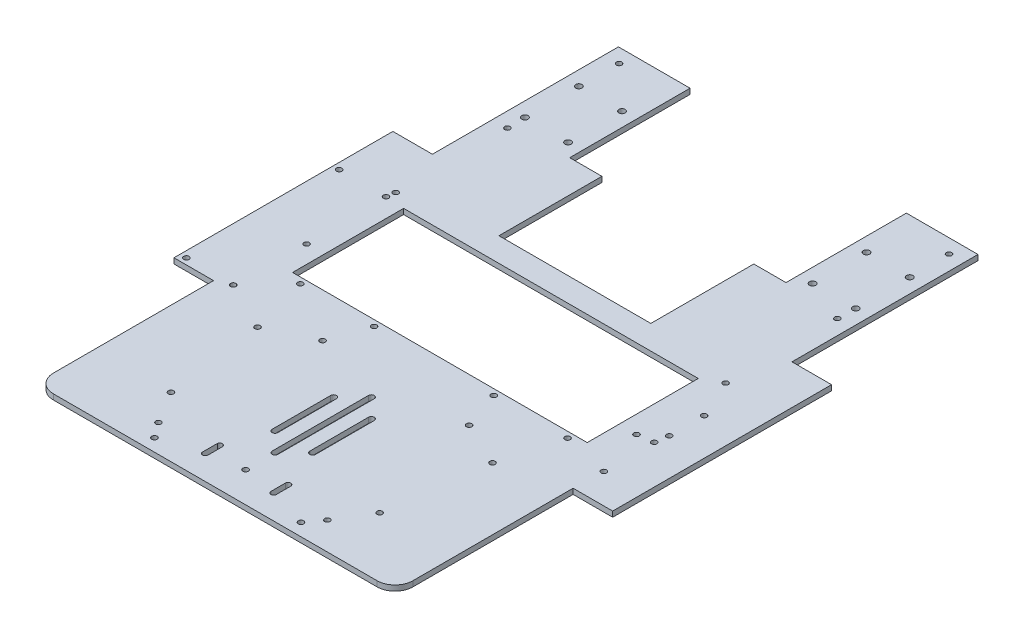
SolidWorks part; units mm, degrees
material "1060 合金"
ref_plane "前视基准面" through (0, 0, 0) normal (0, 0, 1) x (1, 0, 0)
ref_plane "上视基准面" through (0, 0, 0) normal (0, 1, 0) x (1, 0, 0)
ref_plane "右视基准面" through (0, 0, 0) normal (1, 0, 0) x (0, 0, -1)
sketch "草图1" plane through (0, 0, 0) normal (0, 1, 0) x (1, 0, 0)
  line L1 (-100, 187.5) -> (100, 187.5)
  line L2 (-100, 187.5) -> (-100, -187.5)
  line L3 (-100, -187.5) -> (100, -187.5)
  line L4 (100, 187.5) -> (100, -187.5)
  line L5 (-100, 187.5) -> (100, -187.5) construction
  line L6 (-100, -187.5) -> (100, 187.5) construction
  point P0 (0, 0)
  dimension "D1" = 200
  dimension "D2" = 375
extrude "凸台-拉伸1" add sketch "草图1" along normal blind 3
sketch "草图2" plane through (0, 0, 0) normal (0, -1, 0) x (1, 0, 0)
  circle A0 centre (-68, -157.5) radius 1.75
  circle A1 centre (-92, -157.5) radius 1.75
  circle A2 centre (-92, -127.5) radius 1.75
  circle A3 centre (-68, -127.5) radius 1.75
  circle A4 centre (68, -157.5) radius 1.75
  circle A5 centre (92, -157.5) radius 1.75
  circle A6 centre (92, -127.5) radius 1.75
  circle A7 centre (68, -127.5) radius 1.75
extrude "切除-拉伸1" cut sketch "草图2" against normal blind 10
sketch "草图3" plane through (0, 3, 0) normal (0, 1, 0) x (1, 0, 0)
  line L0 (-105, 142.5) -> (105, 142.5) construction
  line L1 (0, 142.5) -> (0, -119.8967) construction
  line L2 (89.8494, 24.4347) -> (-12.8649, 220.1986) construction
  circle A0 centre (0, -119.8967) radius 1.5
  dimension "D1" = 3
extrude "切除-拉伸2" cut sketch "草图3" against normal blind 10
sketch "草图4" plane through (0, 3, 0) normal (0, 1, 0) x (1, 0, 0)
  line L0 (0, -119.8967) -> (19, -119.8967) construction
  circle A0 centre (19, -119.8967) radius 1.5
  circle A1 centre (-19, -119.8967) radius 1.5
  point P4 (0, -119.8967)
  dimension "D2" = 3
  dimension "D3" = 3
  dimension "D4" = 19
  dimension "D1" = 19
extrude "切除-拉伸3" cut sketch "草图4" against normal blind 10
sketch "草图5" plane through (0, 0, 0) normal (0, -1, 0) x (1, 0, 0)
  line L0 (0, 187.5) -> (0, 136.7741) construction
  line L1 (-100, 187.5) -> (100, 187.5) construction
  line L3 (-105, 136.7741) -> (105, 136.7741)
  line L4 (-105, 136.7741) -> (-105, 187.5)
  line L5 (-105, 187.5) -> (105, 187.5)
  line L6 (105, 136.7741) -> (105, 187.5)
  line L7 (-105, 136.7741) -> (105, 187.5) construction
  line L8 (-105, 187.5) -> (105, 136.7741) construction
  point P5 (0, 162.1371)
  dimension "D1" = 210
extrude "切除-拉伸5" cut sketch "草图5" against normal blind 34.39
sketch "草图8" plane through (-100, 0, 0) normal (-1, 0, 0) x (0, 0, 1)
  line L0 (-162.3927, 122.6166) -> (228.9407, 122.6166) construction
  line L1 (31.5492, 79.1374) -> (31.5492, -133.9071) construction
  line L2 (31.5492, -13.3403) -> (-28.0757, -13.3403) construction
  line L3 (-31.7127, 11.4579) -> (-31.7127, -35.1628) construction
  line L4 (-89.9817, 86.9955) -> (-89.9817, -35.1628) construction
  line L5 (34.4197, 14.3679) -> (37.8722, 3)
  line L6 (136.7741, 3) -> (-187.5, 3) construction
  line L7 (37.8722, 3) -> (25.2261, 3)
  line L8 (28.6786, 14.3679) -> (25.2261, 3)
  arc A0 (34.4197, 14.3679) -> (28.6786, 14.3679) centre (31.5492, 13.4961) ccw
  circle A1 centre (31.5492, 13.4961) radius 1.5
  point P19 (31.5492, 3)
  dimension "D1" = 6
  dimension "D2" = 3
extrude "凸台-拉伸2" add sketch "草图8" against normal blind 3
sketch "草图9" plane through (0, 0, 0) normal (0, -1, 0) x (1, 0, 0)
  line L1 (-81.9415, -19.3479) -> (81.9415, -19.3479)
  line L2 (-81.9415, -19.3479) -> (-81.9415, 55.6521)
  line L3 (-81.9415, 55.6521) -> (81.9415, 55.6521)
  line L4 (81.9415, -19.3479) -> (81.9415, 55.6521)
  line L5 (-81.9415, -19.3479) -> (81.9415, 55.6521) construction
  line L6 (-81.9415, 55.6521) -> (81.9415, -19.3479) construction
  point P0 (0, 18.1521)
  dimension "D1" = 75
extrude "切除-拉伸6" cut sketch "草图9" against normal blind 10
sketch "草图10" plane through (0, 0, 0) normal (0, -1, 0) x (1, 0, 0)
  line L0 (0, -63.2891) -> (0, -187.5) construction
  line L1 (100, -187.5) -> (-100, -187.5) construction
  line L2 (-60.1571, -120.5533) -> (-42.2388, -120.5533)
  line L4 (-60.1571, -120.5533) -> (-60.1571, -187.5)
  line L5 (-60.1571, -187.5) -> (60.1571, -187.5)
  line L6 (60.1571, -120.5533) -> (60.1571, -187.5)
  line L7 (-42.2388, -68.35) -> (60.1571, -187.5) construction
  line L8 (-60.1571, -187.5) -> (42.2388, -68.35) construction
  line L9 (-42.2388, -120.5533) -> (-42.2388, -63.2891)
  line L10 (-42.2388, -63.2891) -> (42.2388, -63.2891)
  line L11 (42.2388, -120.5533) -> (42.2388, -63.2891)
  line L12 (60.1571, -120.5533) -> (42.2388, -120.5533)
  point P4 (0, -117.5)
extrude "切除-拉伸7" cut sketch "草图10" against normal blind 3
sketch "草图11" plane through (0, 3, 0) normal (0, 1, 0) x (1, 0, 0)
  circle A0 centre (-91.7562, 179.6301) radius 1.5
  circle A1 centre (-91.7562, 117.5) radius 1.5
  circle A2 centre (-91.7562, 55.3699) radius 1.5
  circle A3 centre (91.7562, 55.3699) radius 1.5
  circle A4 centre (91.7562, 117.5) radius 1.5
  circle A5 centre (91.7562, 179.6301) radius 1.5
extrude "切除-拉伸8" cut sketch "草图11" against normal blind 6
sketch "草图12" plane through (0, 3, 0) normal (0, 1, 0) x (1, 0, 0)
  circle A0 centre (-91.7562, 5.8084) radius 1.5
  circle A1 centre (91.7562, 5.8084) radius 1.5
extrude "切除-拉伸9" cut sketch "草图12" against normal blind 3
sketch "草图14" plane through (0, 3, 0) normal (0, 1, 0) x (1, 0, 0)
  line L0 (81.9415, 19.3479) -> (81.9415, 49.289)
  line L1 (-81.9415, 49.289) -> (-81.9415, 54.8514)
  line L2 (-81.9415, 49.289) -> (-81.9415, 19.3479)
  line L3 (-81.9415, 19.3479) -> (81.9415, 19.3479)
  line L5 (-81.9415, 54.8514) -> (81.9415, 54.8514)
  line L6 (81.9415, 54.8514) -> (81.9415, 49.289)
extrude "切除-拉伸10" cut sketch "草图14" against normal blind 163.8
sketch "草图16" plane through (0, 3, 0) normal (0, 1, 0) x (1, 0, 0)
  line L0 (-86.368, -11.8049) -> (87.5033, -11.8049)
  line L1 (87.5033, -11.8049) -> (87.5033, -62.5063)
  line L2 (87.5033, -62.5063) -> (-86.368, -62.5063)
  line L3 (-86.368, -62.5063) -> (-86.368, -11.8049)
extrude "凸台-拉伸4" add sketch "草图16" against normal blind 3
sketch "草图18" plane through (-100, 0, 0) normal (-1, 0, 0) x (0, 0, 1)
  line L0 (-187.5, 3) -> (25.2261, 3) construction
  line L1 (-187.5, 0) -> (136.7741, 0) construction
  line L2 (-84.0425, 3) -> (37.706, 3)
  line L3 (-84.0425, 3) -> (-84.0425, 0)
  line L4 (-84.0425, 0) -> (37.706, 0)
  line L5 (37.706, 3) -> (37.706, 0)
extrude "凸台-拉伸5" add sketch "草图18" along normal blind 22
sketch "草图19" plane through (-100, 0, 0) normal (-1, 0, 0) x (0, 0, 1)
  line L0 (37.8722, 3) -> (136.7741, 3) construction
  line L1 (22.9673, 24.5564) -> (40.2459, 24.5564)
  line L2 (22.9673, 24.5564) -> (22.9673, 3)
  line L3 (22.9673, 3) -> (40.2459, 3)
  line L4 (40.2459, 24.5564) -> (40.2459, 3)
  line L5 (22.9673, 24.5564) -> (40.2459, 3) construction
  line L6 (22.9673, 3) -> (40.2459, 24.5564) construction
  point P0 (31.6066, 13.7782)
extrude "切除-拉伸11" cut sketch "草图19" against normal blind 22
mirror "镜向1" about plane through (0, 0, 0) normal (1, 0, 0) of "凸台-拉伸5"
sketch "草图20" plane through (0, 0, 0) normal (0, -1, 0) x (1, 0, 0)
  circle A0 centre (-92.4373, 34.3016) radius 1.5
  circle A1 centre (-118.5127, 34.3016) radius 1.5
  circle A2 centre (-92.4373, -50.6696) radius 1.5
  circle A3 centre (-118.5127, -50.6696) radius 1.5
extrude "切除-拉伸12" cut sketch "草图20" against normal blind 5
sketch "草图21" plane through (0, 3, 0) normal (0, 1, 0) x (1, 0, 0)
  circle A0 centre (101.4936, 33.6733) radius 1.5
  circle A1 centre (101.4936, 14.236) radius 1.5
  circle A2 centre (100.4679, -21.0893) radius 1.5
  circle A3 centre (100.4679, 6.9384) radius 1.5
  point P12 (0, 0)
  point P13 (0, 0)
  point P14 (0, 0)
  point P15 (0, 0)
extrude "切除-拉伸13" cut sketch "草图21" against normal blind 6
sketch "草图22" plane through (0, 3, 0) normal (0, 1, 0) x (1, 0, 0)
  line L0 (-81.9415, 49.9559) -> (81.9415, 49.9559)
  line L1 (-81.9415, 54.8514) -> (-81.9415, -11.8049) construction
  line L2 (81.9415, -11.8049) -> (81.9415, 54.8514) construction
  line L3 (81.9415, 49.9559) -> (81.9415, 54.8514)
  line L4 (81.9415, 54.8514) -> (-81.9415, 54.8514) construction
  line L5 (81.9415, 54.8514) -> (-81.9415, 54.8514)
  line L6 (-81.9415, 54.8514) -> (-81.9415, 49.9559)
extrude "凸台-拉伸6" add sketch "草图22" against normal up to surface (3 mm away) up to face at (101.4936, 0, -12.736)
sketch "草图23" plane through (0, 0, 0) normal (0, -1, 0) x (1, 0, 0)
  line L0 (0, 76.779) -> (0, 36.8339) construction
  line L1 (-12.1, 93.0464) -> (-12.1, 60.4263)
  line L2 (-8.9, 60.4263) -> (-8.9, 93.0464)
  line L3 (8.9, 93.0464) -> (8.9, 60.4263)
  line L4 (12.1, 60.4263) -> (12.1, 93.0464)
  line L5 (-1.6, 103.5464) -> (-1.6, 49.9263)
  line L6 (1.6, 49.9263) -> (1.6, 103.5464)
  arc A0 (8.9, 60.4263) -> (12.1, 60.4263) centre (10.5, 60.4263) ccw
  arc A1 (-12.1, 60.4263) -> (-8.9, 60.4263) centre (-10.5, 60.4263) ccw
  arc A2 (-1.6, 49.9263) -> (1.6, 49.9263) centre (0, 49.9263) ccw
  arc A4 (-8.9, 93.0464) -> (-12.1, 93.0464) centre (-10.5, 93.0464) ccw
  arc A6 (12.1, 93.0464) -> (8.9, 93.0464) centre (10.5, 93.0464) ccw
  arc A7 (1.6, 103.5464) -> (-1.6, 103.5464) centre (0, 103.5464) ccw
extrude "切除-拉伸14" cut sketch "草图23" against normal blind 10
sketch "草图24" plane through (0, 3, 0) normal (0, 1, 0) x (1, 0, 0)
  line L0 (-20.5, -119.8967) -> (-20.5, -115.1045)
  line L1 (-17.5, -119.8967) -> (-17.5, -115.1045)
  line L2 (-17.5, -119.8967) -> (-17.5, -123.2927)
  line L3 (-20.5, -123.2927) -> (-20.5, -119.8967)
  line L4 (0, -118.3967) -> (0, -124.1043) construction
  line L5 (20.5, -123.2927) -> (20.5, -119.8967)
  line L6 (17.5, -119.8967) -> (17.5, -123.2927)
  line L7 (17.5, -119.8967) -> (17.5, -115.1045)
  line L8 (20.5, -119.8967) -> (20.5, -115.1045)
  circle A0 centre (-19, -119.8967) radius 1.5 construction
  arc A1 (-17.5, -115.4096) -> (-20.5, -115.4096) centre (-19, -115.257) ccw
  arc A2 (-20.5, -123.2927) -> (-17.5, -123.2927) centre (-19, -123.2927) ccw
  circle A3 centre (0, -119.8967) radius 1.5 construction
  arc A4 (20.5, -123.2927) -> (17.5, -123.2927) centre (19, -123.2927) cw
  arc A5 (17.5, -115.4096) -> (20.5, -115.4096) centre (19, -115.257) cw
extrude "切除-拉伸15" cut sketch "草图24" against normal blind 10 contours L3 A2 L2 L1 A1 L0 | A5 L7 L6 A4 L5 L8
sketch "草图25" plane through (0, 3, 0) normal (0, 1, 0) x (1, 0, 0)
  circle A0 centre (-74.308, -15.1266) radius 1.5
  circle A1 centre (-33.25, -15.1266) radius 1.5
  circle A2 centre (33.25, -15.1266) radius 1.5
  circle A3 centre (74.308, -15.1266) radius 1.5
extrude "切除-拉伸16" cut sketch "草图25" against normal blind 5
sketch "草图26" plane through (0, 3, 0) normal (0, 1, 0) x (1, 0, 0)
  circle A0 centre (-65.342, -47.8897) radius 1.5
  circle A1 centre (65.342, -47.8897) radius 1.5
  circle A2 centre (46.9865, -121.3869) radius 1.5
  circle A3 centre (-46.9865, -121.3869) radius 1.5
extrude "切除-拉伸17" cut sketch "草图26" against normal blind 10
sketch "草图27" plane through (0, 3, 0) normal (0, 1, 0) x (1, 0, 0)
  line L0 (0, -158.3179) -> (0, -24.9992) construction
  line L2 (-40.75, -36.322) -> (40.75, -36.322) construction
  line L3 (-40.75, -36.322) -> (-40.75, -129.822) construction
  line L4 (-40.75, -129.822) -> (40.75, -129.822) construction
  line L5 (40.75, -36.322) -> (40.75, -129.822) construction
  line L6 (-40.75, -36.322) -> (40.75, -129.822) construction
  line L7 (-40.75, -129.822) -> (40.75, -36.322) construction
  circle A0 centre (-40.75, -36.322) radius 1.5
  circle A1 centre (40.75, -36.322) radius 1.5
  circle A2 centre (40.75, -129.822) radius 1.5
  circle A3 centre (-40.75, -129.822) radius 1.5
  point P3 (0, -83.072)
  dimension "D3" = 3
  dimension "D4" = 3
  dimension "D5" = 3
  dimension "D6" = 3
  dimension "D1" = 81.5
  dimension "D2" = 93.5
extrude "切除-拉伸18" cut sketch "草图27" against normal blind 3
sketch "草图28" plane through (0, 3, 0) normal (0, 1, 0) x (1, 0, 0)
  circle A0 centre (-58.0337, -103.3479) radius 1.5
  circle A1 centre (58.0337, -103.3479) radius 1.5
extrude "切除-拉伸19" cut sketch "草图28" against normal blind 3
fillet "圆角1" radius 10 2 edges at (100, 1.5, 136.7741) (-100, 1.5, 136.7741)
